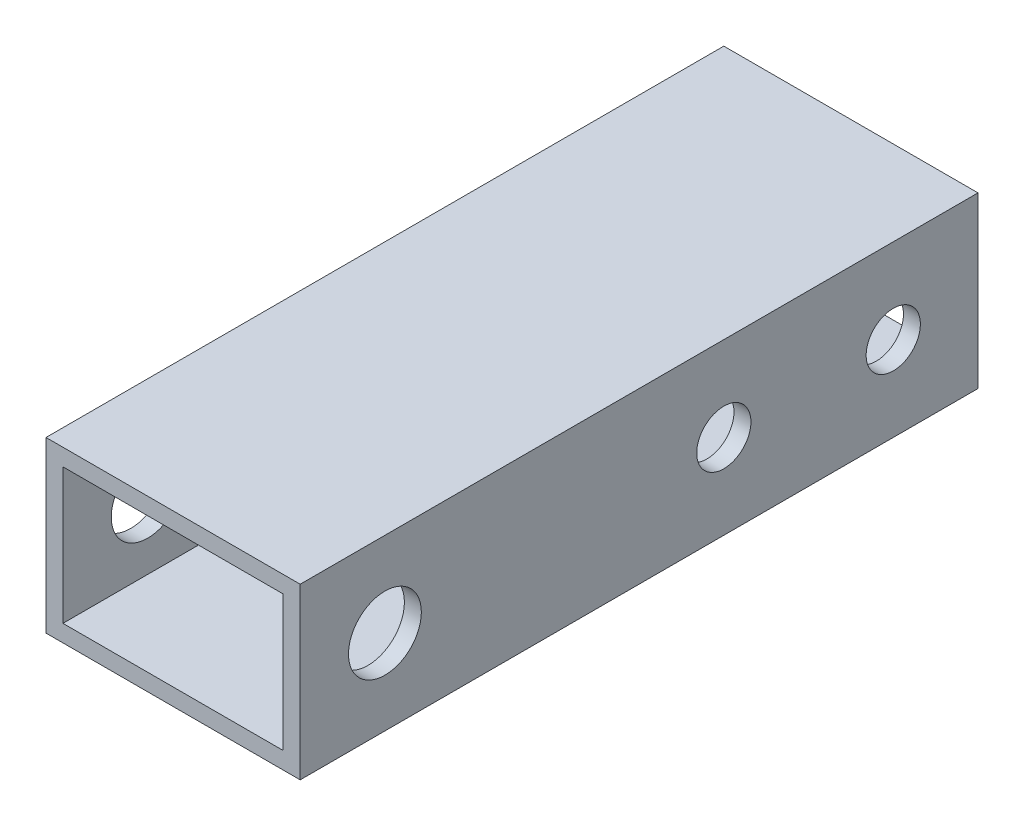
SolidWorks part; units mm, degrees
material "5052-H34"
ref_plane "正面" through (0, 0, 0) normal (0, 0, 1) x (1, 0, 0)
ref_plane "平面" through (0, 0, 0) normal (0, 1, 0) x (1, 0, 0)
ref_plane "右側面" through (0, 0, 0) normal (1, 0, 0) x (0, 0, -1)
sketch "ｽｹｯﾁ1" plane through (0, 0, 0) normal (0, 0, 1) x (1, 0, 0)
  line L1 (0, 0) -> (15, 0)
  line L2 (0, 0) -> (0, 10)
  line L3 (0, 10) -> (15, 10)
  line L4 (15, 0) -> (15, 10)
  dimension "D1" = 10
  dimension "D2" = 15
extrude "押し出し-薄板1" add sketch "ｽｹｯﾁ1" along normal blind 40 thin thin type one direction reverse wall 1
sketch "ｽｹｯﾁ2" plane through (15, 0, 0) normal (1, 0, 0) x (0, 0, -1)
  line L0 (0, 5) -> (-40, 5) construction
  line L1 (0, 0) -> (0, 10) construction
  line L2 (-40, 0) -> (-40, 10) construction
  circle A0 centre (-5, 5) radius 1.6
  circle A1 centre (-15, 5) radius 1.6
  circle A2 centre (-35, 5) radius 2.15
  dimension "D1" = 3.2
  dimension "D2" = 5
  dimension "D3" = 10
  dimension "D4" = 4.3
  dimension "D5" = 5
extrude "ｶｯﾄ - 押し出し1" cut sketch "ｽｹｯﾁ2" against normal up to surface (15 mm away) up to face at (0, 5, 20)
